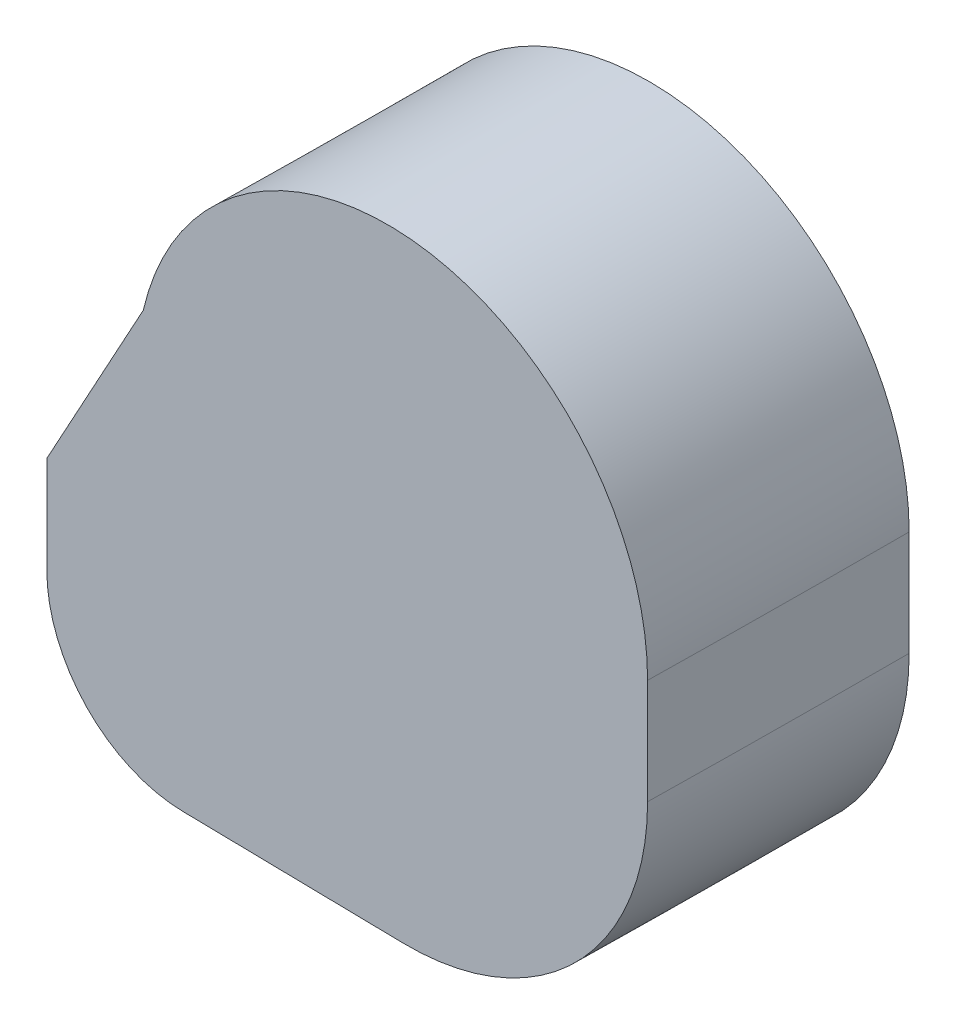
SolidWorks part; units mm, degrees
ref_plane "Front Plane" through (0, 0, 0) normal (0, 0, 1) x (1, 0, 0)
ref_plane "Top Plane" through (0, 0, 0) normal (0, 1, 0) x (1, 0, 0)
ref_plane "Right Plane" through (0, 0, 0) normal (1, 0, 0) x (0, 0, -1)
other "Configuration Table"
sketch "Sketch4" plane through (0, 0, 0) normal (0, 0, 1) x (1, 0, 0)
  line L0 (0, 0) -> (2.0574, 0)
  line L1 (-132.0384, 8.3845) -> (-132.0384, -7.9578) construction
  line L2 (4.3434, 2.286) -> (4.3434, 3.2512)
  line L3 (-1.27, 1.27) -> (-1.27, 2.1602)
  line L4 (-0.3688, 3.796) -> (-1.27, 2.1602)
  arc A0 (2.0574, 0) -> (4.3434, 2.286) centre (2.0574, 2.286) ccw
  arc A1 (4.3434, 3.2512) -> (-0.3688, 3.796) centre (1.9558, 3.2512) ccw
  arc A2 (0, 0) -> (-1.27, 1.27) centre (0, 1.27) cw
  dimension "D2" = 2.286
  dimension "D3" = 0.9652
  dimension "D4" = 2.3876
  dimension "D5" = 1.27
  dimension "D1" = 2.0574
  dimension "D6" = 0.8902
  dimension "D7" = 130.7684
revolve "Revolve1" add sketch "Sketch4" angle 1 about L1
fillet "Fillet1" [suppressed] radius 2.54
